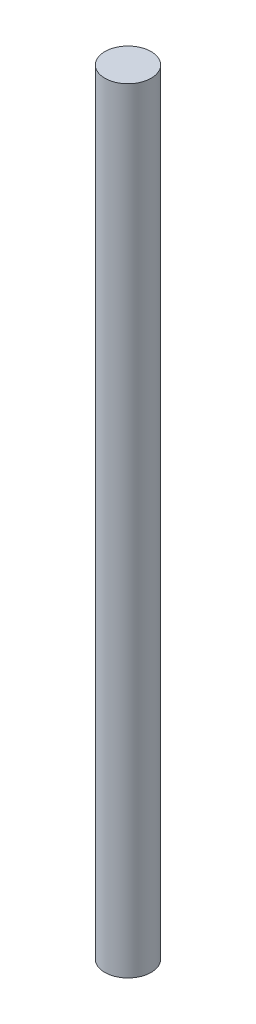
SolidWorks part; units mm, degrees
ref_plane "Front Plane" through (0, 0, 0) normal (0, 0, 1) x (1, 0, 0)
ref_plane "Top Plane" through (0, 0, 0) normal (0, 1, 0) x (1, 0, 0)
ref_plane "Right Plane" through (0, 0, 0) normal (1, 0, 0) x (0, 0, -1)
sketch "Sketch1" plane through (0, 0, 0) normal (0, 0, 1) x (1, 0, 0)
  line L0 (0, 0) -> (0, 100.4435)
  line L1 (0, 100.4435) -> (26.9478, 100.4435) construction
sketch "Sketch2" plane through (0, 0, 0) normal (0, 1, 0) x (1, 0, 0)
  circle A0 centre (0, 0) radius 3
  dimension "D1" = 6
sweep "Sweep1" add profiles "Sketch2" path "Sketch1"
